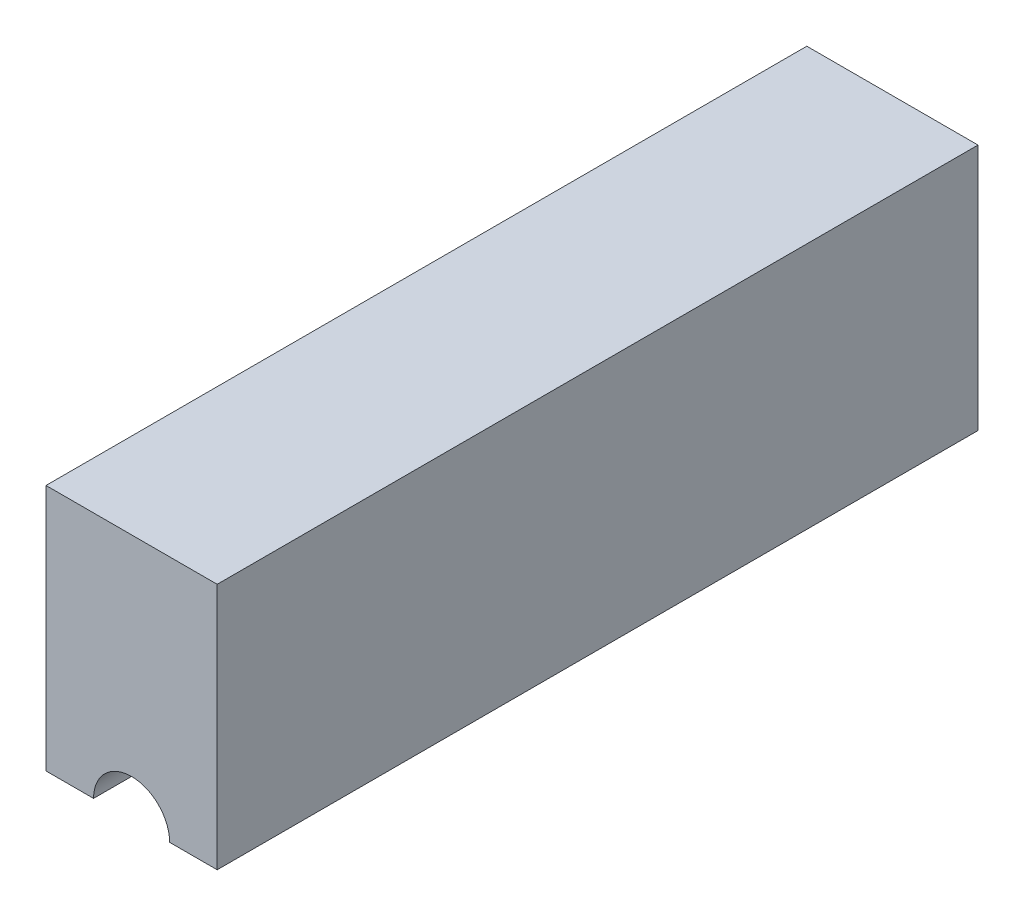
SolidWorks part; units mm, degrees
ref_plane "Front" through (0, 0, 0) normal (0, 0, 1) x (1, 0, 0)
ref_plane "Top" through (0, 0, 0) normal (0, 1, 0) x (1, 0, 0)
ref_plane "Right" through (0, 0, 0) normal (1, 0, 0) x (0, 0, -1)
other "Configuration Table"
sketch "Sketch1" plane through (0, 0, 0) normal (0, 0, 1) x (1, 0, 0)
  line L0 (32.5, 0) -> (45, 0)
  line L1 (0, 0) -> (12.5, 0)
  line L2 (0, 0) -> (0, 65)
  line L3 (0, 65) -> (45, 65)
  line L4 (45, 0) -> (45, 65)
  arc A0 (32.5, 0) -> (12.5, 0) centre (22.5, 0) ccw
  dimension "D3" = 10
  dimension "D1" = 45
  dimension "D2" = 65
  dimension "D4" = 22.5
extrude "Base-Extrude" add sketch "Sketch1" along normal mid plane 200
